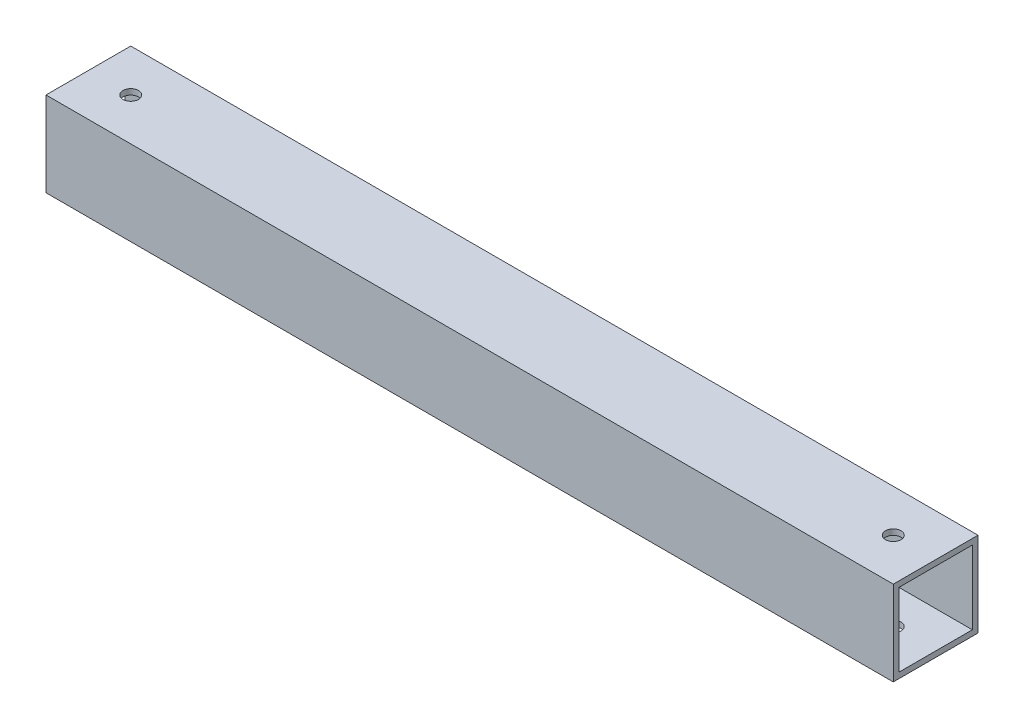
SolidWorks part; units mm, degrees
ref_plane "Front Plane" through (0, 0, 0) normal (0, 0, 1) x (1, 0, 0)
ref_plane "Top Plane" through (0, 0, 0) normal (0, 1, 0) x (1, 0, 0)
ref_plane "Right Plane" through (0, 0, 0) normal (1, 0, 0) x (0, 0, -1)
sketch "Sketch1" plane through (0, 0, 0) normal (1, 0, 0) x (0, 0, -1)
  line L1 (15, 15) -> (-15, 15)
  line L2 (15, 15) -> (15, -15)
  line L3 (15, -15) -> (-15, -15)
  line L4 (-15, 15) -> (-15, -15)
  line L5 (15, 15) -> (-15, -15) construction
  line L6 (15, -15) -> (-15, 15) construction
  line L7 (-13, 13) -> (13, 13)
  line L8 (-13, 13) -> (-13, -13)
  line L9 (-13, -13) -> (13, -13)
  line L10 (13, 13) -> (13, -13)
  line L11 (-13, 13) -> (13, -13) construction
  line L12 (-13, -13) -> (13, 13) construction
  point P0 (0, 0)
  point P5 (0, 0)
  dimension "D1" = 30
  dimension "D2" = 30
  dimension "D3" = 2
extrude "Boss-Extrude1" add sketch "Sketch1" along normal mid plane 300
sketch "Sketch2" plane through (0, 0, 0) normal (0, 1, 0) x (1, 0, 0)
  line L0 (150, 15) -> (150, -15) construction
  circle A0 centre (135, 0) radius 2.75
  dimension "D1" = 5.5
  dimension "D2" = 15
extrude "Cut-Extrude1" cut sketch "Sketch2" against normal through all both and the other way through all
mirror "Mirror1" about plane through (0, 0, 0) normal (1, 0, 0) of "Cut-Extrude1"
equation "\"D2@Sketch1\"=\"w\""
equation "\"D1@Sketch1\"=\"w\""
equation "\"t\"= 2"
equation "\"w\"= 30"
equation "\"D3@Sketch1\"=\"t\""
equation "\"D2@Sketch2\"=\"w\"/2"
